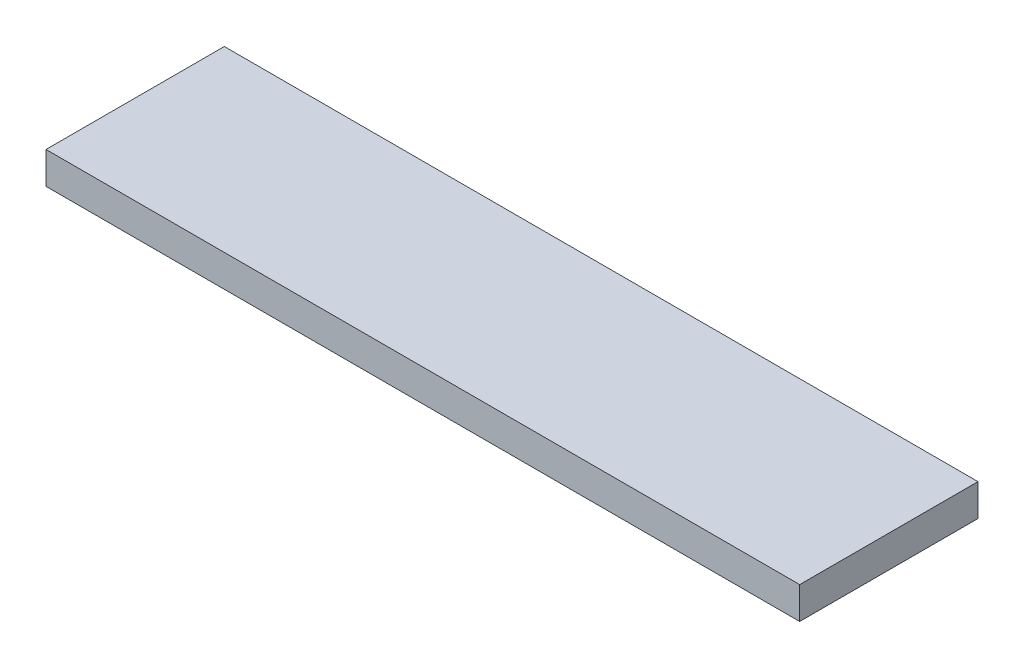
SolidWorks part; units mm, degrees
ref_plane "前视基准面" through (0, 0, 0) normal (0, 0, 1) x (1, 0, 0)
ref_plane "上视基准面" through (0, 0, 0) normal (0, 1, 0) x (1, 0, 0)
ref_plane "右视基准面" through (0, 0, 0) normal (1, 0, 0) x (0, 0, -1)
sketch "草图1" plane through (0, 0, 0) normal (0, 1, 0) x (1, 0, 0)
  line L1 (0, 0) -> (224, 0)
  line L2 (0, 0) -> (0, -53)
  line L3 (0, -53) -> (224, -53)
  line L4 (224, 0) -> (224, -53)
  dimension "D1" = 224
  dimension "D2" = 53
extrude "凸台-拉伸1" add sketch "草图1" along normal blind 9.5
